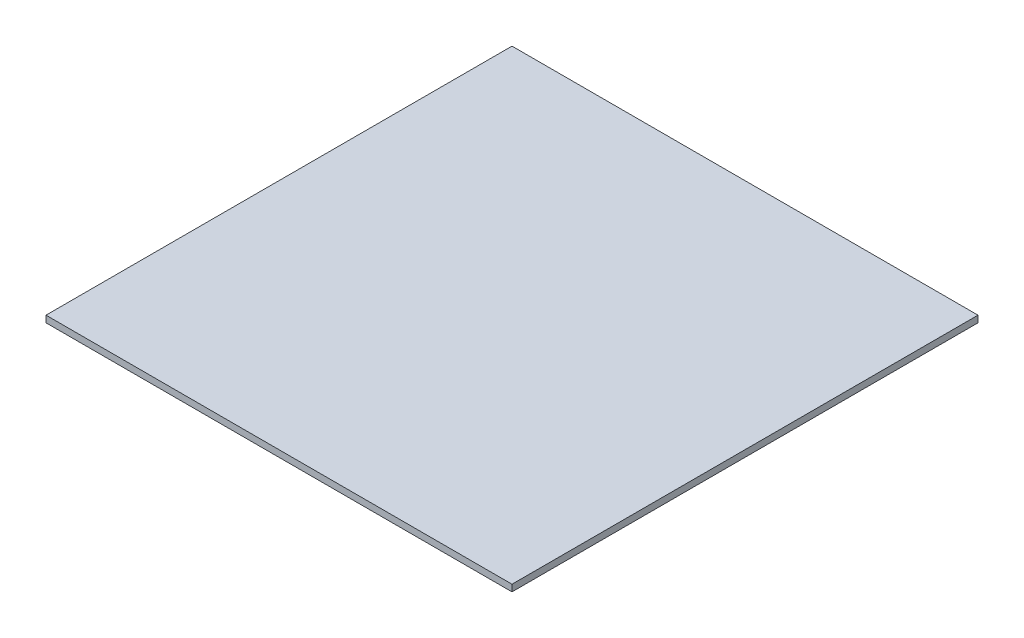
SolidWorks part; units mm, degrees
ref_plane "Front Plane" through (0, 0, 0) normal (0, 0, 1) x (1, 0, 0)
ref_plane "Top Plane" through (0, 0, 0) normal (0, 1, 0) x (1, 0, 0)
ref_plane "Right Plane" through (0, 0, 0) normal (1, 0, 0) x (0, 0, -1)
sketch "Sketch1" plane through (0, 0, 0) normal (0, 1, 0) x (1, 0, 0)
  line L1 (1750, -1750) -> (-1750, -1750)
  line L2 (1750, -1750) -> (1750, 1750)
  line L3 (1750, 1750) -> (-1750, 1750)
  line L4 (-1750, -1750) -> (-1750, 1750)
  line L5 (1750, -1750) -> (-1750, 1750) construction
  line L6 (1750, 1750) -> (-1750, -1750) construction
  point P0 (0, 0)
  dimension "D1" = 3500
  dimension "D2" = 3500
extrude "Boss-Extrude1" add sketch "Sketch1" along normal blind 50
sketch "Sketch2" plane through (0, 0, 0) normal (0, -1, 0) x (1, 0, 0)
  line L1 (375, -375) -> (-375, -375)
  line L2 (375, -375) -> (375, 375)
  line L3 (375, 375) -> (-375, 375)
  line L4 (-375, -375) -> (-375, 375)
  line L5 (375, -375) -> (-375, 375) construction
  line L6 (375, 375) -> (-375, -375) construction
  point P0 (0, 0)
  dimension "D1" = 750
  dimension "D2" = 750
extrude "Cut-Extrude1" cut sketch "Sketch2" against normal blind 10
